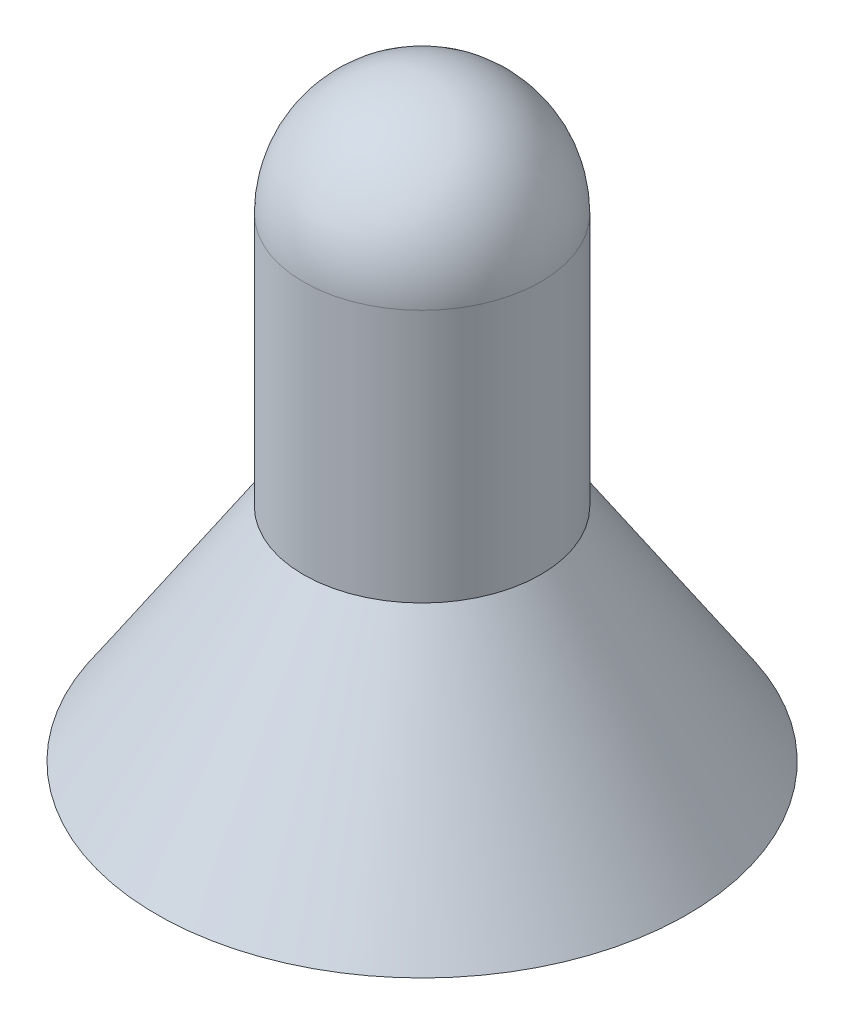
SolidWorks part; units mm, degrees
ref_plane "Front" through (0, 0, 0) normal (0, 0, 1) x (1, 0, 0)
ref_plane "Top" through (0, 0, 0) normal (0, 1, 0) x (1, 0, 0)
ref_plane "Right" through (0, 0, 0) normal (1, 0, 0) x (0, 0, -1)
sketch "草图1" plane through (0, 0, 0) normal (1, 0, 0) x (0, 0, -1)
  line L0 (0, 0) -> (0, 21.6795) construction
  line L3 (20, 37.2665) -> (44.7198, 0)
  line L4 (20, 80) -> (20, 37.2665)
  line L5 (16.6667, 35.0554) -> (39.9198, 0)
  line L6 (-8.0426, 0) -> (11.8047, 0) construction
  line L8 (-44.7198, 0) -> (-39.9198, 0)
  line L9 (39.9198, 0) -> (44.7198, 0)
  line L10 (0, 44) -> (0, 100)
  line L11 (0, 44) -> (0, 100) construction
  arc A0 (20, 80) -> (0, 100) centre (0, 80) ccw
  arc A2 (16.6667, 35.0554) -> (0, 44) centre (0, 24) ccw
revolve "旋转3" add sketch "草图1" angle 360 about L10
